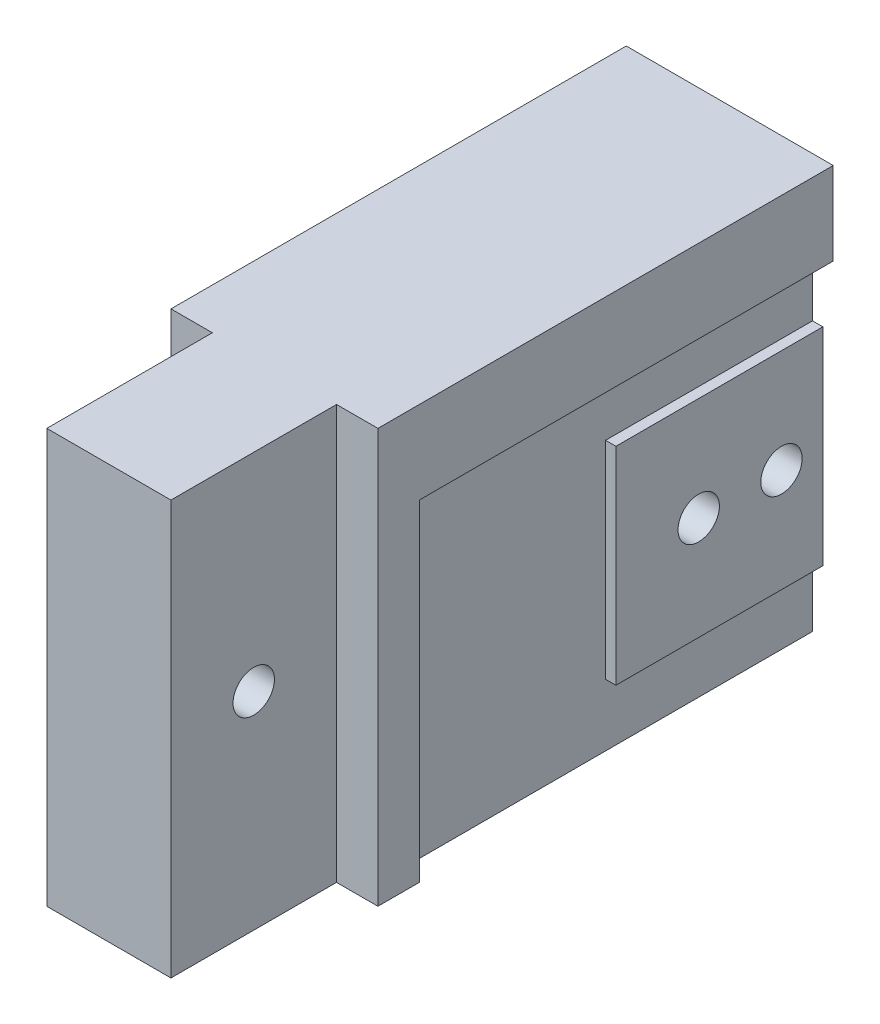
SolidWorks part; units mm, degrees
ref_plane "Ebene vorne" through (0, 0, 0) normal (0, 0, 1) x (1, 0, 0)
ref_plane "Ebene oben" through (0, 0, 0) normal (0, 1, 0) x (1, 0, 0)
ref_plane "Ebene rechts" through (0, 0, 0) normal (1, 0, 0) x (0, 0, -1)
sketch "Skizze1" plane through (0, 0, 0) normal (1, 0, 0) x (0, 0, -1)
  line L1 (-106.9542, 40.537) -> (43.0458, 40.537)
  line L2 (-106.9542, 40.537) -> (-106.9542, -59.463)
  line L3 (-106.9542, -59.463) -> (43.0458, -59.463)
  line L4 (43.0458, 40.537) -> (43.0458, -59.463)
  dimension "D1" = 150
  dimension "D2" = 100
extrude "Aufsatz-Linear austragen1" add sketch "Skizze1" along normal blind 50
sketch "Skizze2" plane through (50, 0, 0) normal (1, 0, 0) x (0, 0, -1)
  line L1 (43.0458, -59.463) -> (-56.9542, -59.463)
  line L2 (43.0458, -59.463) -> (43.0458, 20.537)
  line L3 (43.0458, 20.537) -> (-56.9542, 20.537)
  line L4 (-56.9542, -59.463) -> (-56.9542, 20.537)
  dimension "D1" = 100
  dimension "D2" = 80
extrude "Schnitt-Linear austragen1" cut sketch "Skizze2" against normal blind 5
sketch "Skizze3" plane through (45, 0, 0) normal (1, 0, 0) x (0, 0, -1)
  line L0 (43.0458, -59.463) -> (43.0458, 20.537) construction
  line L1 (-56.9542, -59.463) -> (43.0458, -59.463) construction
  line L2 (43.0458, 5.537) -> (-6.9542, 5.537)
  line L3 (43.0458, 5.537) -> (43.0458, -44.463)
  line L4 (43.0458, -44.463) -> (-6.9542, -44.463)
  line L5 (-6.9542, 5.537) -> (-6.9542, -44.463)
  dimension "D1" = 50
  dimension "D2" = 50
  dimension "D3" = 15
extrude "Aufsatz-Linear austragen2" add sketch "Skizze3" along normal blind 2.5
sketch "Skizze4" plane through (47.5, 0, 0) normal (1, 0, 0) x (0, 0, -1)
  line L0 (43.0458, -44.463) -> (43.0458, 5.537) construction
  circle A0 centre (33.0458, -19.463) radius 5
  circle A1 centre (13.0458, -19.463) radius 5
  dimension "D1" = 10
  dimension "D2" = 20
extrude "Schnitt-Linear austragen2" cut sketch "Skizze4" against normal blind 10
sketch "Skizze5" plane through (0, 0, 106.9542) normal (0, 0, 1) x (1, 0, 0)
  line L0 (50, -59.463) -> (0, -59.463) construction
  line L1 (0, 40.537) -> (10, 40.537)
  line L2 (0, 40.537) -> (0, -59.463)
  line L3 (0, -59.463) -> (10, -59.463)
  line L4 (10, 40.537) -> (10, -59.463)
  line L5 (25, 40.537) -> (25, -59.463) construction
  line L6 (50, 40.537) -> (0, 40.537) construction
  line L7 (50, -59.463) -> (40, -59.463)
  line L8 (40, 40.537) -> (40, -59.463)
  line L9 (50, 40.537) -> (40, 40.537)
  line L10 (50, 40.537) -> (50, -59.463)
  dimension "D1" = 10
extrude "Schnitt-Linear austragen3" cut sketch "Skizze5" against normal blind 40
sketch "Skizze6" plane through (40, 0, 0) normal (1, 0, 0) x (0, 0, -1)
  line L0 (-106.9542, 40.537) -> (-106.9542, -59.463) construction
  circle A0 centre (-86.9542, -9.463) radius 5
  dimension "D1" = 20
extrude "Schnitt-Linear austragen4" cut sketch "Skizze6" against normal blind 40
